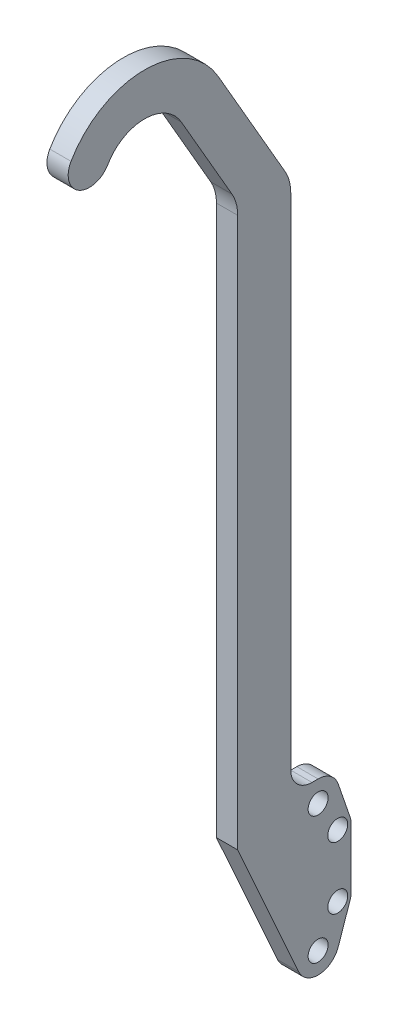
SolidWorks part; units mm, degrees
ref_plane "Front Plane" through (0, 0, 0) normal (0, 0, 1) x (1, 0, 0)
ref_plane "Top Plane" through (0, 0, 0) normal (0, 1, 0) x (1, 0, 0)
ref_plane "Right Plane" through (0, 0, 0) normal (1, 0, 0) x (0, 0, -1)
sketch "Sketch1" plane through (0, 0, 0) normal (1, 0, 0) x (0, 0, -1)
  line L0 (-8.7313, -21.6489) -> (-26.9875, 19.05)
  line L1 (-26.9875, 19.05) -> (-26.9875, 186.7592)
  line L2 (-26.9875, 186.7592) -> (-43.8119, 215.9)
  line L4 (-32.8134, 222.25) -> (-11.1125, 184.6629)
  line L5 (-11.1125, 184.6629) -> (-11.1125, 25.4)
  line L9 (-65.809, 215.9) -> (-69.3194, 209.8198) construction
  line L10 (-65.809, 155.8008) -> (-80.932, 129.6071) construction
  line L11 (-69.9334, 110.5571) -> (-39.6875, 110.5571) construction
  line L12 (-28.689, 129.6071) -> (-43.8119, 155.8008) construction
  line L13 (-7.9375, -87.9564) -> (7.9375, -87.9564) construction
  line L14 (-54.8105, 149.4508) -> (-69.9334, 123.2571) construction
  line L15 (-69.9334, 123.2571) -> (-39.6875, 123.2571) construction
  line L16 (-39.6875, 123.2571) -> (-54.8105, 149.4508) construction
  line L17 (-2.9375, -19.05) -> (-2.9375, 19.05) construction
  line L18 (7.9375, -87.9564) -> (7.9375, -76.9784) construction
  line L19 (-7.9375, -87.9564) -> (-7.9375, -76.9784) construction
  line L20 (-2.9375, 25.4) -> (-11.1125, 25.4)
  line L22 (3.0681, -21.1128) -> (6.691, -10.5649)
  line L23 (2.9375, -9.2757) -> (2.9375, 9.2757) construction
  line L24 (3.0681, 21.1128) -> (6.691, 10.5649)
  line L25 (6.9062, 9.2757) -> (6.9062, -9.2757)
  arc A2 (-43.8119, 215.9) -> (-65.809, 215.9) centre (-54.8105, 209.55) ccw
  arc A3 (-65.809, 215.9) -> (-76.8075, 222.25) centre (-71.3083, 219.075) cw
  arc A4 (-76.8075, 222.25) -> (-32.8134, 222.25) centre (-54.8105, 209.55) cw
  arc A7 (-43.8119, 155.8008) -> (-65.809, 155.8008) centre (-54.8105, 149.4508) ccw construction
  arc A9 (-80.932, 129.6071) -> (-69.9334, 110.5571) centre (-69.9334, 123.2571) ccw construction
  arc A10 (-39.6875, 110.5571) -> (-28.689, 129.6071) centre (-39.6875, 123.2571) ccw construction
  circle A11 centre (-54.8105, 131.9883) radius 8.7313 construction
  arc A12 (-8.7313, -21.6489) -> (3.0681, -21.1128) centre (-2.9375, -19.05) ccw
  arc A13 (6.691, -10.5649) -> (6.9062, -9.2757) centre (2.9375, -9.2757) ccw
  arc A14 (3.0681, 21.1128) -> (-2.9375, 25.4) centre (-2.9375, 19.05) ccw
  arc A15 (6.691, 10.5649) -> (6.9062, 9.2757) centre (2.9375, 9.2757) cw
  circle A16 centre (-2.9375, -19.05) radius 5.702 construction
  circle A17 centre (2.9375, -9.2757) radius 5.702 construction
  point P0 (0, -87.9564)
  point P2 (-54.8105, 156.4386)
  point P3 (-2.9375, 19.05)
  point P4 (-2.9375, -19.05)
  point P14 (2.9375, -9.2757)
  point P21 (-2.9375, 0)
  point P48 (-54.8105, 131.9883)
  point P50 (2.9375, 9.2757)
  point P51 (2.9375, 0)
  point P65 (-54.8105, 222.25)
  dimension "D2" = 38.1
  dimension "D3" = 15.875
  dimension "D10" = 222.25
  dimension "D11" = 12.7
  dimension "D13" = 12.7
  dimension "D15" = 11.1125
  dimension "D9" = 12.7
  dimension "D7" = 12.7
  dimension "D17" = 11.4041
  dimension "D18" = 7.9375
  dimension "D4" = 5
  dimension "D5" = 15.875
  dimension "D6" = 5
  dimension "D8" = 150
  dimension "D12" = 60
  dimension "D14" = 38.8937
  dimension "D16" = 38.1
extrude "Boss-Extrude1" add sketch "Sketch1" along normal mid plane 6.35
fillet "Fillet1" radius 12.7 2 edges at (0, 184.6629, 11.1125) (0, 186.7592, 26.9875)
sketch "Sketch2" plane through (3.175, 0, 0) normal (1, 0, 0) x (0, 0, -1)
  circle A0 centre (-2.9375, 19.05) radius 2.9845
  circle A1 centre (2.9375, -9.2757) radius 2.9845
  circle A2 centre (-2.9375, -19.05) radius 2.9845
  circle A3 centre (2.9375, 9.2757) radius 2.9845
  dimension "D1" = 5.969
extrude "Cut-Extrude1" cut sketch "Sketch2" against normal through all
fillet "Fillet2" radius 6.35 1 edges at (0, 25.4, 11.1125)
